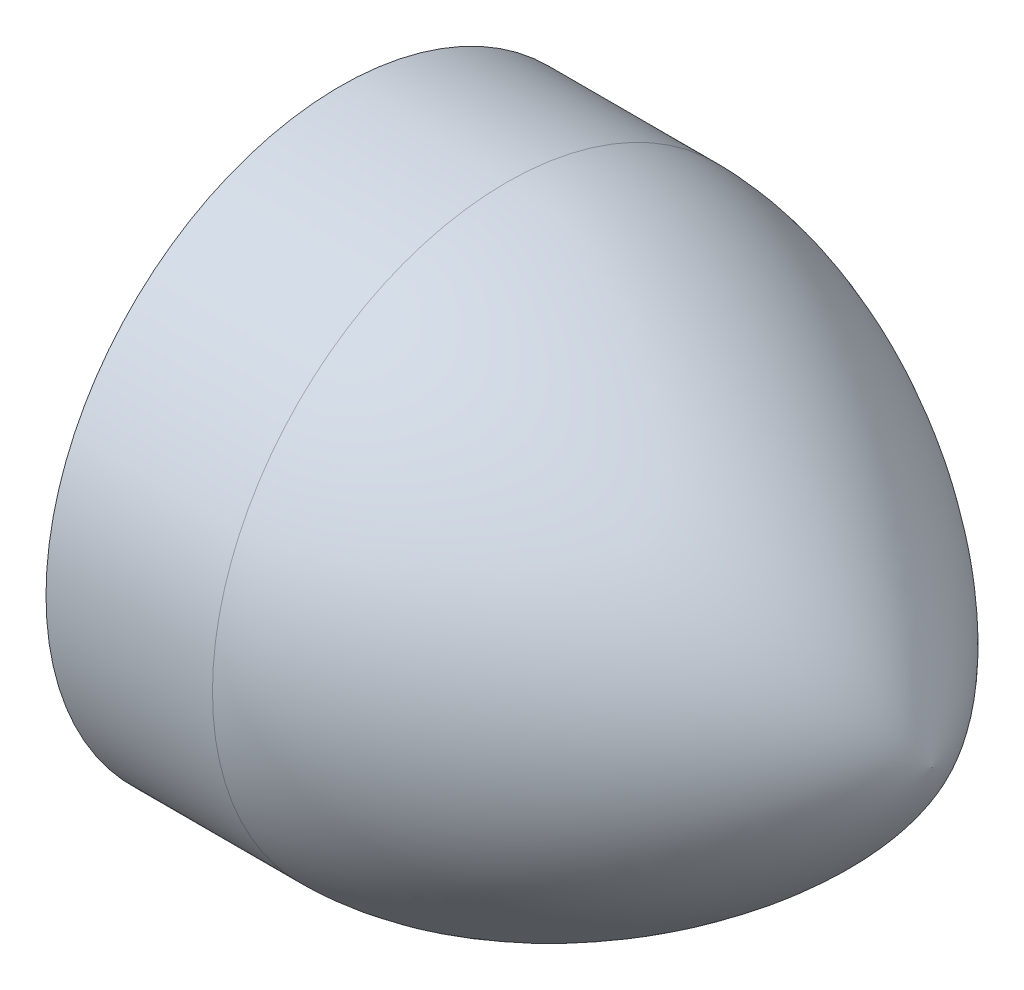
SolidWorks part; units mm, degrees
ref_plane "Front Plane" through (0, 0, 0) normal (0, 0, 1) x (1, 0, 0)
ref_plane "Top Plane" through (0, 0, 0) normal (0, 1, 0) x (1, 0, 0)
ref_plane "Right Plane" through (0, 0, 0) normal (1, 0, 0) x (0, 0, -1)
sketch "Sketch1" plane through (0, 0, 0) normal (0, 0, 1) x (1, 0, 0)
  line L0 (0, 0) -> (0, 10.1205)
  line L1 (0, 10.1205) -> (5.7292, 10.1205)
  line L2 (0, 0) -> (20.3542, 0)
  spline S0 degree 3 poles (5.7292, 10.1205) (11.6575, 10.1448) (19.4255, 4.1877) (20.3542, 0) knots 0 0 0 0 1 1 1 1
revolve "Revolve1" add sketch "Sketch1" angle 360 about L2
